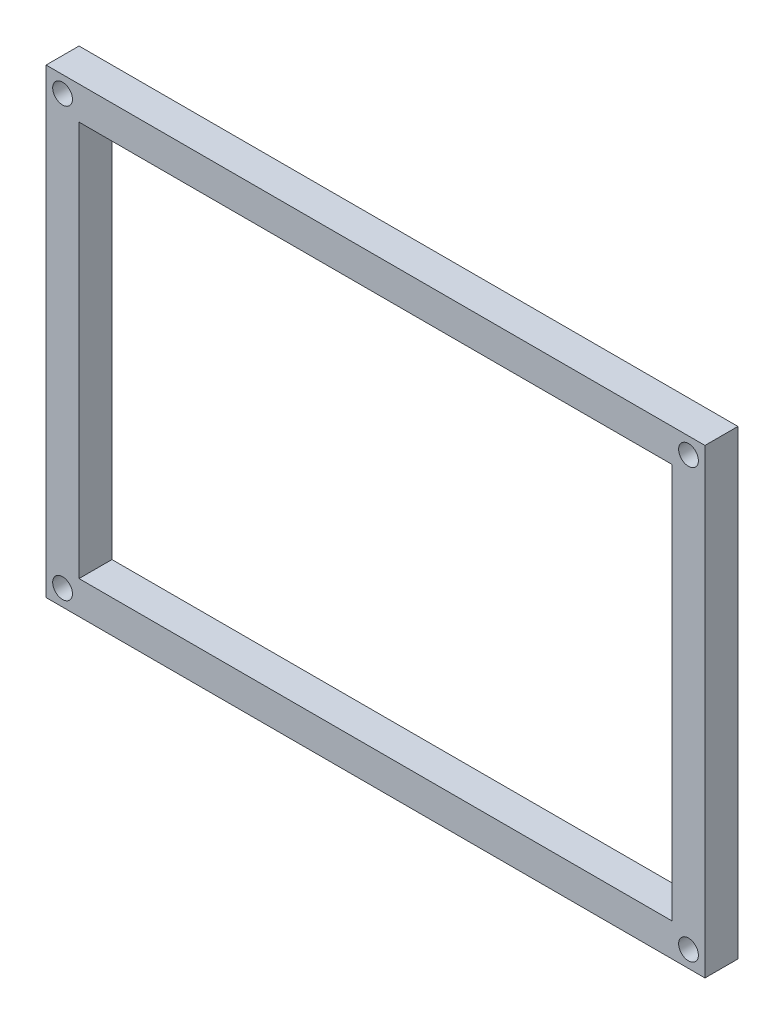
SolidWorks part; units mm, degrees
ref_plane "Front Plane" through (0, 0, 0) normal (0, 0, 1) x (1, 0, 0)
ref_plane "Top Plane" through (0, 0, 0) normal (0, 1, 0) x (1, 0, 0)
ref_plane "Right Plane" through (0, 0, 0) normal (1, 0, 0) x (0, 0, -1)
sketch "Sketch1" plane through (0, 0, 0) normal (0, 0, 1) x (1, 0, 0)
  line L0 (8.5, 51.5) -> (67.75, 51.5)
  line L1 (0, 0) -> (90, 0)
  line L2 (0, 0) -> (0, 60)
  line L3 (0, 60) -> (90, 60)
  line L4 (90, 0) -> (90, 60)
  line L5 (8.5, 51.5) -> (8.5, 8.5)
  line L6 (8.5, 8.5) -> (67.75, 8.5)
  line L7 (67.75, 51.5) -> (67.75, 8.5)
  line L8 (45, 60) -> (45, 65) construction
  line L9 (-5, -5) -> (95, -5)
  line L10 (-5, -5) -> (-5, 65)
  line L11 (-5, 65) -> (95, 65)
  line L12 (95, -5) -> (95, 65)
  line L13 (0, 30) -> (-5, 30) construction
  line L14 (45, 0) -> (45, -5) construction
  line L15 (90, 30) -> (95, 30) construction
  line L16 (0, 60) -> (-5, 65) construction
  line L17 (76.5, 44.5) -> (86.5, 44.5)
  line L18 (76.5, 44.5) -> (76.5, 36.5)
  line L19 (76.5, 36.5) -> (86.5, 36.5)
  line L20 (86.5, 44.5) -> (86.5, 36.5)
  line L21 (76.5, 34.5) -> (86.5, 34.5)
  line L22 (76.5, 34.5) -> (76.5, 26.5)
  line L23 (76.5, 26.5) -> (86.5, 26.5)
  line L24 (86.5, 34.5) -> (86.5, 26.5)
  line L25 (76.5, 24.5) -> (86.5, 24.5)
  line L26 (76.5, 24.5) -> (76.5, 16.5)
  line L27 (76.5, 16.5) -> (86.5, 16.5)
  line L28 (86.5, 24.5) -> (86.5, 16.5)
  line L29 (76.5, 14.5) -> (86.5, 14.5)
  line L30 (76.5, 14.5) -> (76.5, 6.5)
  line L31 (76.5, 6.5) -> (86.5, 6.5)
  line L32 (86.5, 14.5) -> (86.5, 6.5)
  line L33 (76.5, 46.5) -> (86.5, 46.5)
  line L34 (76.5, 46.5) -> (76.5, 54.5)
  line L35 (76.5, 54.5) -> (86.5, 54.5)
  line L36 (86.5, 46.5) -> (86.5, 54.5)
  line L37 (95, 65) -> (90, 60) construction
  line L38 (95, -5) -> (90, 0) construction
  line L39 (0, 0) -> (-5, -5) construction
  circle A0 centre (-2.5, -2.5) radius 1.5
  circle A1 centre (-2.5, 62.5) radius 1.5
  circle A2 centre (92.5, 62.5) radius 1.5
  circle A3 centre (92.5, -2.5) radius 1.5
  dimension "D16" = 3
  dimension "D1" = 90
  dimension "D2" = 60
  dimension "D3" = 8.5
  dimension "D4" = 8.5
  dimension "D5" = 8.5
  dimension "D6" = 22.25
  dimension "D7" = 5
  dimension "D8" = 10
  dimension "D9" = 8
  dimension "D10" = 6.5
  dimension "D11" = 16.5
  dimension "D12" = 26.5
  dimension "D13" = 36.5
  dimension "D14" = 46.5
  dimension "D15" = 3.5
extrude "Boss-Extrude1" add sketch "Sketch1" along normal blind 5 contours L9 L12 L11 L10 A3 A2 A1 A0 L4 L1 L2 L3
